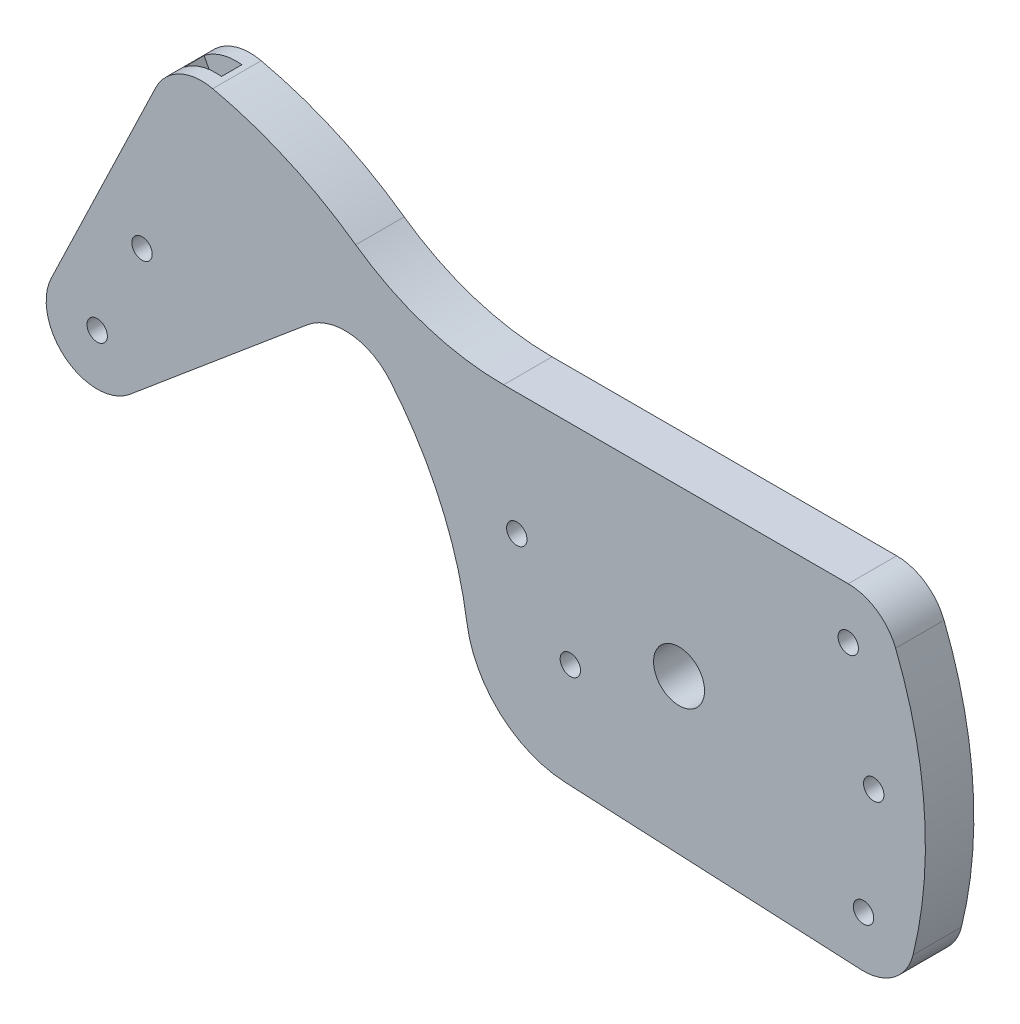
SolidWorks part; units mm, degrees
ref_plane "Front Plane" through (0, 0, 0) normal (0, 0, 1) x (1, 0, 0)
ref_plane "Top Plane" through (0, 0, 0) normal (0, 1, 0) x (1, 0, 0)
ref_plane "Right Plane" through (0, 0, 0) normal (1, 0, 0) x (0, 0, -1)
sketch "Sketch1" plane through (0, 0, 0) normal (0, 0, 1) x (1, 0, 0)
  line L1 (-5, -5) -> (5, -5) construction
  line L2 (-5, -5) -> (-5, 5) construction
  line L3 (-5, 5) -> (5, 5) construction
  line L4 (5, -5) -> (5, 5) construction
  line L5 (-5, -5) -> (5, 5) construction
  line L6 (-5, 5) -> (5, -5) construction
  line L7 (35.6989, -31.9883) -> (-22.3088, -29.1817)
  line L9 (-114.3299, 24.3337) -> (-123.1299, 6.0337)
  line L10 (-107.6899, -5.9604) -> (-72.8648, 23.2613)
  line L11 (-114.3299, 24.3337) -> (-102.6393, 48.6449)
  line L16 (-65.4725, 14.4515) -> (-108.3178, -21.5) construction
  line L17 (50.9822, -33.5) -> (-177.2181, -33.5) construction
  line L20 (-34.3975, 32.3) -> (33.1822, 32.3)
  circle A0 centre (0, 0) radius 5
  circle A1 centre (-31.8178, 8.3) radius 2
  circle A2 centre (-21.3178, -8.7) radius 2
  circle A3 centre (33.1822, 22.3) radius 2
  circle A4 centre (38.1822, -0.1) radius 2
  circle A5 centre (36.1822, -22) radius 2
  circle A6 centre (36.1822, -22) radius 2 construction
  circle A7 centre (38.1822, -0.1) radius 2 construction
  circle A8 centre (33.1822, 22.3) radius 2 construction
  circle A9 centre (-31.8178, 8.3) radius 2 construction
  circle A10 centre (-21.3178, -8.7) radius 2 construction
  arc A12 (-41.605, -11.6848) -> (-22.3088, -29.1817) centre (-21.3178, -8.7) ccw
  arc A13 (32.976, -31.8566) -> (28.2895, 32.3) centre (-34.3029, -4.5217) ccw construction
  arc A14 (45.8883, -24.4068) -> (42.4751, 25.9934) centre (-34.3029, -4.5217) ccw
  arc A15 (35.6989, -31.9883) -> (45.8883, -24.4068) centre (36.1822, -22) ccw
  arc A16 (42.4751, 25.9934) -> (33.1822, 32.3) centre (33.1822, 22.3) ccw
  circle A17 centre (-105.3178, 20) radius 2
  circle A18 centre (-34.3029, -4.5217) radius 82.6199 construction
  circle A19 centre (-114.1178, 1.7) radius 2
  circle A21 centre (-105.3178, 20) radius 2 construction
  circle A22 centre (-114.1178, 1.7) radius 2 construction
  circle A23 centre (-105.3178, 20) radius 10 construction
  arc A24 (-123.1299, 6.0337) -> (-107.6899, -5.9604) centre (-114.1178, 1.7) ccw
  arc A27 (-91.4485, 54.071) -> (-102.6393, 48.6449) centre (-93.6271, 44.3112) ccw
  circle A31 centre (-34.3029, -4.5217) radius 72.6199 construction
  arc A32 (-41.605, -11.6848) -> (-56.6627, 21.8438) centre (-108.3178, -21.5) ccw
  arc A33 (-31.0644, -26.7412) -> (-91.4485, 54.071) centre (-108.3178, -21.5) ccw
  arc A34 (-63.4016, 41.5721) -> (-34.3975, 32.3) centre (-34.3975, 82.3) ccw
  arc A35 (-56.6627, 21.8438) -> (-72.8648, 23.2613) centre (-65.4725, 14.4515) ccw
  circle A36 centre (-65.4725, 14.4515) radius 10.5004 construction
  circle A37 centre (-108.3178, -21.5) radius 67.4309 construction
  circle A38 centre (-108.3178, -21.5) radius 77.4309 construction
  circle A39 centre (-108.3178, -21.5) radius 10.5004 construction
  circle A40 centre (-108.3178, -21.5) radius 11.5004 construction
  circle A41 centre (0, 0) radius 33 construction
  point P35 (50.3427, -4.5217)
  point P37 (37.1696, 16.7103)
  point P54 (-36.0565, -0.0269)
  point P75 (-40.8381, -1.4887)
  dimension "D1" = 10
  dimension "D3" = 10
  dimension "D5" = 50
  dimension "D7" = 40
  dimension "D4" = 10
  dimension "D2" = 10
  dimension "D8" = 1
extrude "Boss-Extrude1" add sketch "Sketch1" along normal mid plane 9.5 contours A0 L4 L3 | A0 L1 L4 | A0 L2 L1 | A0 L3 L2 | A35 A32 A12 A33 A27 L11 L9 A24 L10 A17 A19
sketch "Sketch2" plane through (0, 0, 0) normal (0, 0, 1) x (1, 0, 0)
  line L0 (-93.6271, 44.3112) -> (-96.4023, 53.9184) construction
  line L1 (-78.2271, 18.7618) -> (-72.8648, 23.2613)
  line L2 (-93.6271, 44.3112) -> (-84.6823, 13.3452) construction
  line L3 (-91.6689, 44.8769) -> (-78.2271, 18.7618)
  line L4 (-94.4967, 54.2733) -> (-93.6271, 44.3112) construction
  line L5 (-93.6271, 44.3112) -> (-90.4984, 8.4649) construction
  line L6 (-98.2036, 53.2026) -> (-93.6271, 44.3112) construction
  line L7 (-93.6271, 44.3112) -> (-79.798, 17.4436) construction
  line L8 (-99.8894, 52.1076) -> (-95.5854, 43.7456)
  line L9 (-92.4867, 54.246) -> (-91.6689, 44.8769)
  line L12 (-92.369, 6.8953) -> (-78.2271, 18.7618)
  line L13 (-107.6899, -5.9604) -> (-72.8648, 23.2613) construction
  line L14 (-100.8204, 53.9163) -> (-90.7503, 34.3517) construction
  line L15 (-92.6635, 56.2725) -> (-90.7503, 34.3517) construction
  line L16 (-95.5854, 43.7456) -> (-92.369, 6.8953)
  line L18 (-96.504, 54.2707) -> (-78.2271, 18.7618) construction
  line L19 (-96.504, 54.2707) -> (-92.369, 6.8953) construction
  line L20 (-92.369, 6.8953) -> (-107.6899, -5.9604)
  line L22 (-93.6271, 44.3112) -> (-90.3766, 7.0692) construction
  line L23 (-93.6271, 44.3112) -> (-80.0054, 17.8465) construction
  arc A0 (-92.4867, 54.246) -> (-99.8894, 52.1076) centre (-93.6271, 44.3112) ccw
  arc A1 (-94.4967, 54.2733) -> (-98.2036, 53.2026) centre (-93.6271, 44.3112) ccw construction
  arc A2 (-92.6635, 56.2725) -> (-100.8204, 53.9163) centre (-93.6271, 44.3112) ccw construction
  arc A3 (-91.4485, 54.071) -> (-102.6393, 48.6449) centre (-93.6271, 44.3112) ccw construction
  point P33 (-96.4023, 53.9184)
  dimension "D3" = 7
  dimension "D4" = 20
  dimension "D1" = 2
  dimension "D2" = 2
extrude "Cut-Extrude1" cut sketch "Sketch2" against normal mid plane 4
